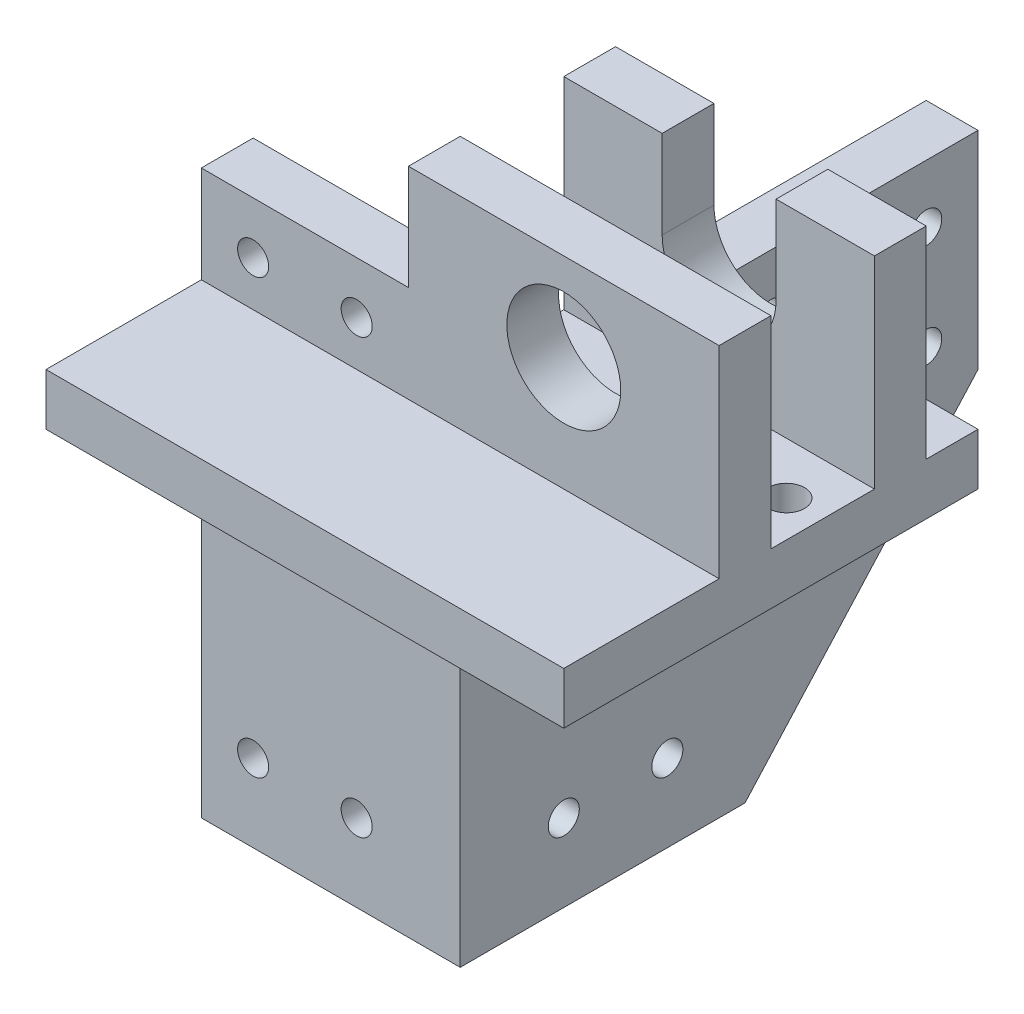
SolidWorks part; units mm, degrees
ref_plane "Front Plane" through (0, 0, 0) normal (0, 0, 1) x (1, 0, 0)
ref_plane "Top Plane" through (0, 0, 0) normal (0, 1, 0) x (1, 0, 0)
ref_plane "Right Plane" through (0, 0, 0) normal (1, 0, 0) x (0, 0, -1)
sketch "Sketch1" plane through (0, 0, 0) normal (0, 1, 0) x (1, 0, 0)
  line L0 (0, 0) -> (100, 0)
  line L1 (100, 0) -> (100, 80)
  line L2 (100, 80) -> (40, 80)
  line L3 (40, 80) -> (40, 40)
  line L4 (40, 40) -> (0, 40)
  line L5 (0, 40) -> (0, 0)
  dimension "D1" = 40
  dimension "D2" = 40
  dimension "D3" = 80
  dimension "D4" = 100
extrude "Boss-Extrude1" add sketch "Sketch1" along normal blind 10
sketch "Sketch2" plane through (0, 10, 0) normal (0, 1, 0) x (1, 0, 0)
  line L0 (40, 80) -> (40, 40) construction
  line L1 (0, 40) -> (40, 40)
  line L2 (0, 40) -> (0, 30)
  line L3 (0, 30) -> (40, 30)
  line L4 (40, 40) -> (40, 30)
  dimension "D1" = 10
extrude "Boss-Extrude2" add sketch "Sketch2" along normal blind 18.71
sketch "Sketch3" plane through (0, 0, 0) normal (0, -1, 0) x (1, 0, 0)
  line L0 (0, -30) -> (50, -30)
  line L1 (0, -40) -> (0, 0) construction
  line L2 (50, -30) -> (50, -80)
  line L3 (100, -80) -> (40, -80) construction
  line L4 (50, -80) -> (40, -80)
  line L5 (40, -80) -> (40, -40)
  line L6 (40, -40) -> (0, -40)
  line L7 (0, -40) -> (0, -30)
  dimension "D1" = 10
  dimension "D2" = 10
extrude "Boss-Extrude3" add sketch "Sketch3" along normal blind 80
sketch "Sketch5" plane through (0, 0, -80) normal (0, 0, -1) x (-1, 0, 0)
  line L1 (-40, 10) -> (-50, 10)
  line L2 (-40, 10) -> (-40, -80)
  line L3 (-40, -80) -> (-50, -80)
  line L4 (-50, 10) -> (-50, -80)
extrude "Boss-Extrude4" add sketch "Sketch5" along normal blind 50
sketch "Sketch6" plane through (40, 0, 0) normal (-1, 0, 0) x (0, 0, 1)
  line L0 (-85, 10) -> (-85, -80) construction
  line L1 (-130, 10) -> (-40, 10) construction
  line L2 (-40, -80) -> (-130, -80) construction
  line L3 (-85, -80) -> (-130, -30)
  line L4 (-130, -80) -> (-130, 10) construction
  line L5 (-130, -30) -> (-130, -80)
  line L6 (-130, -80) -> (-85, -80)
  dimension "D1" = 50
extrude "Cut-Extrude1" cut sketch "Sketch6" against normal blind 10
sketch "Sketch7" plane through (0, 10, 0) normal (0, 1, 0) x (1, 0, 0)
  line L0 (40, 130) -> (40, 40) construction
  line L1 (40, 70) -> (100, 70)
  line L2 (40, 70) -> (40, 60)
  line L3 (40, 60) -> (100, 60)
  line L4 (100, 70) -> (100, 60)
  line L5 (100, 0) -> (100, 80) construction
  line L6 (0, 0) -> (100, 0) construction
  line L7 (40, 40) -> (100, 40)
  line L8 (40, 40) -> (40, 30)
  line L9 (40, 30) -> (100, 30)
  line L10 (100, 40) -> (100, 30)
  dimension "D1" = 10
  dimension "D2" = 10
  dimension "D3" = 40
  dimension "D4" = 20
extrude "Boss-Extrude5" add sketch "Sketch7" along normal blind 39
sketch "Sketch8" plane through (0, 10, 0) normal (0, 1, 0) x (1, 0, 0)
  line L0 (100, 40) -> (100, 60) construction
  line L1 (100, 80) -> (50, 80) construction
  circle A0 centre (47, 50) radius 3.5
  circle A1 centre (93, 50) radius 3.5
  dimension "D2" = 7
  dimension "D1" = 7
  dimension "D3" = 46
  dimension "D4" = 30
extrude "Cut-Extrude2" cut sketch "Sketch8" against normal blind 10
sketch "Sketch9" plane through (50, 0, 0) normal (1, 0, 0) x (0, 0, -1)
  line L0 (50, 0) -> (57, 0)
  line L1 (51.8028, 0) -> (48.1972, 0) construction
  line L2 (80, 0) -> (51.8028, 0) construction
  line L3 (57, 0) -> (57, -6)
  line L4 (57, -6) -> (43, -6)
  line L5 (43, -6) -> (43, 0)
  line L6 (0, 0) -> (80, 0) construction
  line L8 (43, 0) -> (50, 0)
  dimension "D1" = 6
  dimension "D2" = 14
  dimension "D3" = 7
extrude "Cut-Extrude3" cut sketch "Sketch9" against normal blind 10
sketch "Sketch10" plane through (0, 0, -30) normal (0, 0, 1) x (1, 0, 0)
  line L0 (0, 10) -> (100, 10) construction
  line L1 (100, 49) -> (100, 10) construction
  line L2 (0, 28.71) -> (0, 10) construction
  line L3 (0, 28.71) -> (40, 28.71) construction
  line L4 (0, 0) -> (100, 0) construction
  line L5 (50, -80) -> (0, -80) construction
  circle A0 centre (70, 32) radius 11
  circle A1 centre (30, 18.71) radius 3
  circle A2 centre (10, 18.71) radius 3
  circle A3 centre (30, -15) radius 3
  circle A4 centre (10, -15) radius 3
  circle A5 centre (30, -65) radius 3
  circle A6 centre (10, -65) radius 3
  dimension "D1" = 22
  dimension "D4" = 6
  dimension "D2" = 22
  dimension "D3" = 30
  dimension "D5" = 20
  dimension "D6" = 10
  dimension "D7" = 10
  dimension "D8" = 15
  dimension "D9" = 15
extrude "Cut-Extrude4" cut sketch "Sketch10" against normal blind 10
sketch "Sketch11" plane through (50, 0, 0) normal (1, 0, 0) x (0, 0, -1)
  line L0 (30, -80) -> (30, 0) construction
  line L1 (85, -80) -> (30, -80) construction
  line L2 (0, 0) -> (80, 0) construction
  line L3 (130, 10) -> (130, -30) construction
  line L4 (80, 10) -> (80, 0) construction
  line L5 (130, 10) -> (80, 10) construction
  circle A0 centre (50, -15) radius 3
  circle A1 centre (70, -15) radius 3
  circle A4 centre (70, -65) radius 3
  circle A5 centre (50, -65) radius 3
  circle A6 centre (90, -1.3) radius 3
  circle A7 centre (120, -1.3) radius 3
  circle A8 centre (90, -21.3) radius 3
  circle A9 centre (120, -21.3) radius 3
  dimension "D1" = 6
  dimension "D6" = 6
  dimension "D2" = 20
  dimension "D3" = 20
  dimension "D4" = 15
  dimension "D5" = 15
  dimension "D7" = 20
  dimension "D8" = 10
  dimension "D9" = 10
  dimension "D10" = 11.3
extrude "Cut-Extrude5" cut sketch "Sketch11" against normal blind 10
sketch "Sketch12" plane through (0, 0, -70) normal (0, 0, -1) x (-1, 0, 0)
  line L0 (-70, 49) -> (-59, 49)
  line L1 (-100, 49) -> (-40, 49) construction
  line L2 (-59, 49) -> (-59, 32)
  line L3 (-70, 49) -> (-81, 49)
  line L4 (-81, 49) -> (-81, 32)
  line L5 (-100, 10) -> (-50, 10) construction
  arc A0 (-59, 32) -> (-81, 32) centre (-70, 32) cw
  dimension "D1" = 11
  dimension "D2" = 22
  dimension "D3" = 11
  dimension "D4" = 11
extrude "Cut-Extrude6" cut sketch "Sketch12" against normal blind 10
